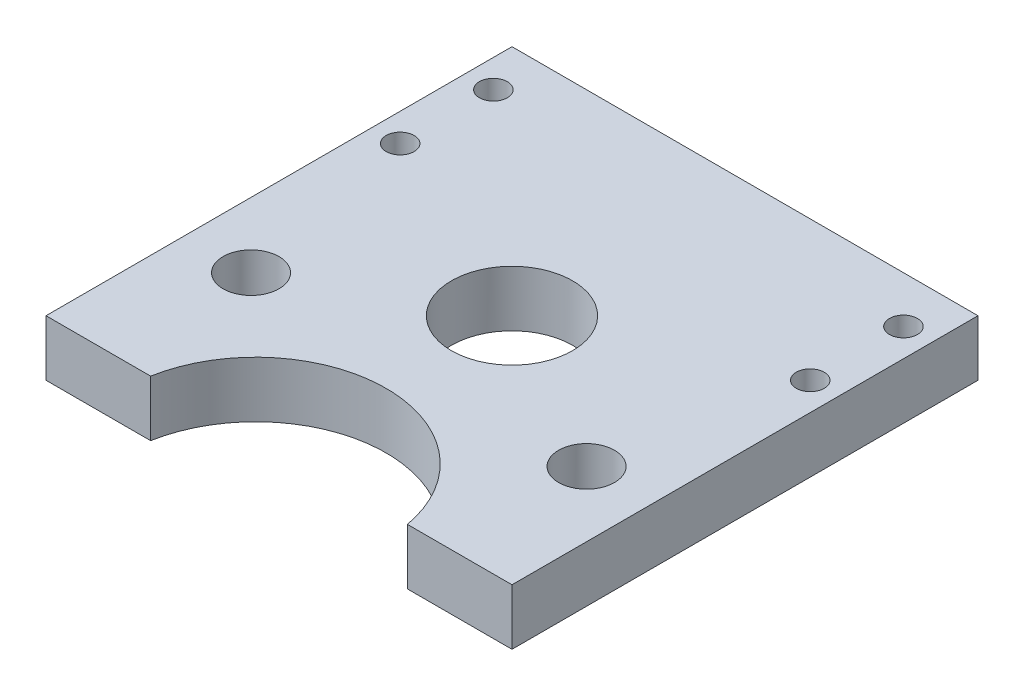
SolidWorks part; units mm, degrees
material "Beech"
ref_plane "Front Plane" through (0, 0, 0) normal (0, 0, 1) x (1, 0, 0)
ref_plane "Top Plane" through (0, 0, 0) normal (0, 1, 0) x (1, 0, 0)
ref_plane "Right Plane" through (0, 0, 0) normal (1, 0, 0) x (0, 0, -1)
sketch "Sketch1" plane through (0, 0, 0) normal (0, 1, 0) x (1, 0, 0)
  line L0 (0, -6.8113) -> (0, 29.9116) construction
  line L1 (-50, 30) -> (50, 30)
  line L2 (-54.3903, 0) -> (55.5839, 0) construction
  line L7 (-50, 30) -> (-50, -70)
  line L8 (-50, -70) -> (50, -70)
  line L9 (50, -70) -> (50, 30)
  point P0 (0, 0)
  dimension "D1" = 30
  dimension "D2" = 50
  dimension "D3" = 100
  dimension "D4" = 100
extrude "Boss-Extrude1" add sketch "Sketch1" along normal blind 12
sketch "Sketch2" plane through (0, 12, 0) normal (0, 1, 0) x (1, 0, 0)
  line L0 (-44, 36.933) -> (-44, -38.3163) construction
  line L1 (44, 34.8909) -> (44, -38.3163) construction
  line L4 (50, 30) -> (-50, 30) construction
  line L5 (-50, 30) -> (-50, -70) construction
  line L6 (50, -70) -> (50, 30) construction
  circle A0 centre (-44, 20) radius 3
  circle A1 centre (-44, 0) radius 3
  circle A2 centre (44, 20) radius 3
  circle A3 centre (44, 0) radius 3
  dimension "D3" = 6
  dimension "D4" = 6
  dimension "D5" = 6
  dimension "D6" = 6
  dimension "D7" = 10
  dimension "D8" = 10
  dimension "D9" = 20
  dimension "D10" = 20
  dimension "D2" = 6
  dimension "D11" = 6
extrude "Cut-Extrude1" cut sketch "Sketch2" against normal up to next
sketch "Sketch3" plane through (0, 12, 0) normal (0, 1, 0) x (1, 0, 0)
  line L0 (0, 33.2699) -> (0, -87.3901) construction
  line L1 (-27.4907, -20) -> (29.5668, -20) construction
  line L6 (-50, -70) -> (50, -70) construction
  circle A4 centre (0, -20) radius 13
  dimension "D9" = 26
  dimension "D10" = 50
extrude "Cut-Extrude2" cut sketch "Sketch3" against normal up to next
sketch "Sketch4" plane through (0, 12, 0) normal (0, 1, 0) x (1, 0, 0)
  line L0 (-50, -70) -> (50, -70) construction
  line L1 (0, -42.4453) -> (0, -79.4161) construction
  circle A0 centre (-36, -40) radius 6
  circle A1 centre (36, -40) radius 6
  dimension "D1" = 12
  dimension "D2" = 12
  dimension "D3" = 36
  dimension "D4" = 36
  dimension "D5" = 30
  dimension "D6" = 30
extrude "Cut-Extrude3" cut sketch "Sketch4" against normal up to next
sketch "Sketch5" plane through (0, 12, 0) normal (0, 1, 0) x (1, 0, 0)
  line L0 (-52.0439, -75) -> (38.9568, -75) construction
  line L1 (-50, -70) -> (50, -70) construction
  line L2 (0, -30.6827) -> (0, -91.6932) construction
  circle A0 centre (0, -75) radius 28
  dimension "D2" = 56
  dimension "D1" = 5
extrude "Cut-Extrude4" cut sketch "Sketch5" against normal up to next
